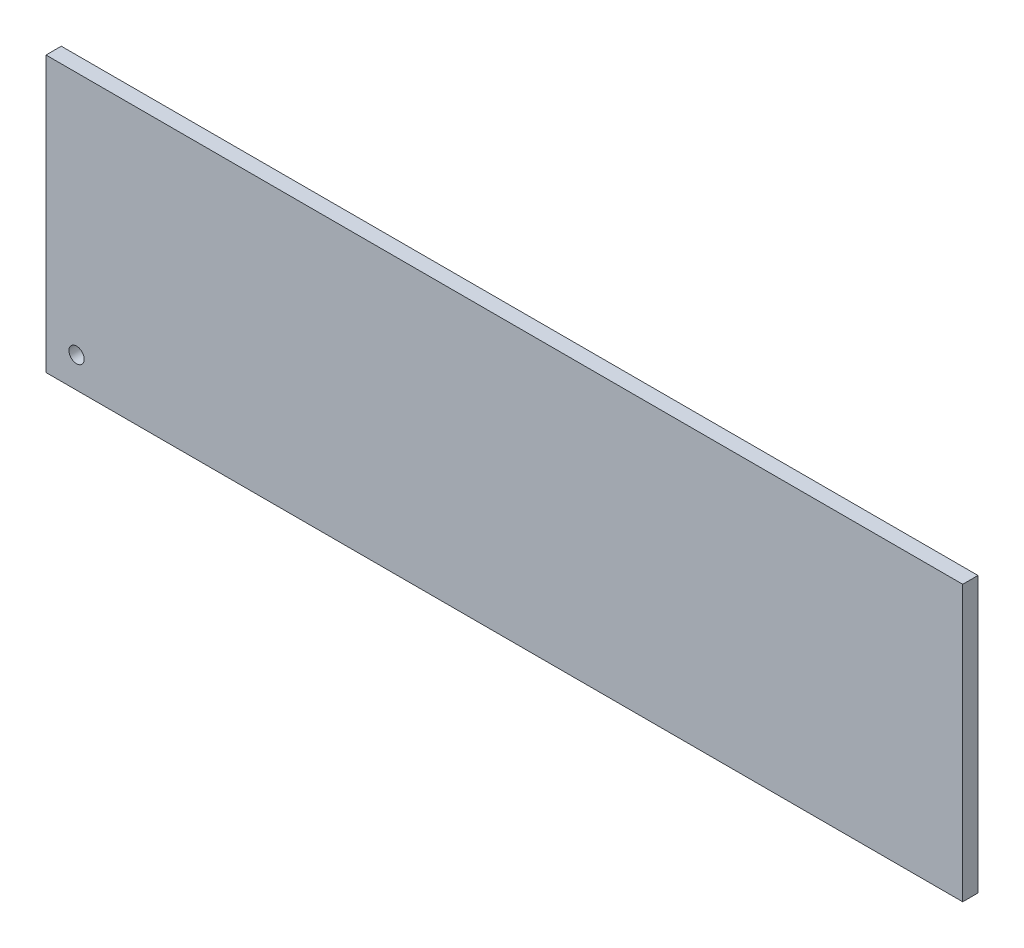
SolidWorks part; units mm, degrees
ref_plane "Plan de face" through (0, 0, 0) normal (0, 0, 1) x (1, 0, 0)
ref_plane "Plan de dessus" through (0, 0, 0) normal (0, 1, 0) x (1, 0, 0)
ref_plane "Plan de droite" through (0, 0, 0) normal (1, 0, 0) x (0, 0, -1)
sketch "Esquisse1" plane through (0, 0, 0) normal (0, 0, 1) x (1, 0, 0)
  line L1 (0, 0) -> (300, 0)
  line L2 (0, 0) -> (0, 90)
  line L3 (0, 90) -> (300, 90)
  line L4 (300, 0) -> (300, 90)
  dimension "D1" = 300
  dimension "D2" = 90
extrude "Boss.-Extru.1" add sketch "Esquisse1" along normal mid plane 5
sketch "Esquisse2" plane through (0, 0, 2.5) normal (0, 0, 1) x (1, 0, 0)
  line L0 (0, 0) -> (300, 0) construction
  line L1 (0, 90) -> (0, 0) construction
  circle A0 centre (10, 10) radius 2.5
  dimension "D1" = 5
  dimension "D2" = 10
  dimension "D3" = 10
extrude "Enlèv. mat.-Extru.1" cut sketch "Esquisse2" against normal through all
